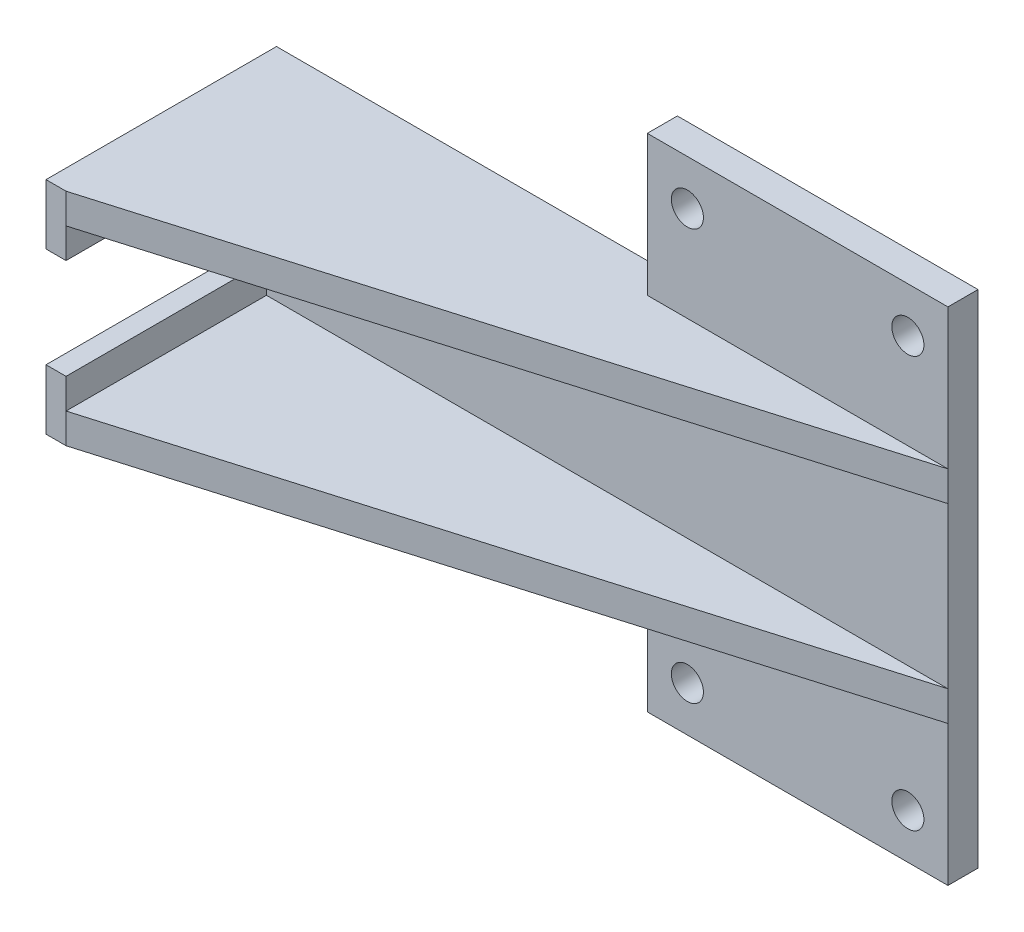
SolidWorks part; units mm, degrees
ref_plane "前视基准面" through (0, 0, 0) normal (0, 0, 1) x (1, 0, 0)
ref_plane "上视基准面" through (0, 0, 0) normal (0, 1, 0) x (1, 0, 0)
ref_plane "右视基准面" through (0, 0, 0) normal (1, 0, 0) x (0, 0, -1)
other "Configuration Table"
sketch "草图1" plane through (0, 0, 0) normal (0, 0, 1) x (1, 0, 0)
  line L0 (-40, -15) -> (-110.8867, -15) construction
  line L1 (-10, 10) -> (-40, 10)
  line L2 (-10, 10) -> (-10, -40)
  line L3 (-10, -40) -> (-40, -40)
  line L4 (-40, 10) -> (-40, -7)
  line L5 (-40, -23) -> (-40, -40)
  line L6 (-80, -23) -> (-40, -23)
  line L7 (-80, -23) -> (-80, -7)
  line L8 (-80, -7) -> (-40, -7)
  line L10 (-80, -23) -> (-40, -7) construction
  line L11 (-80, -7) -> (-40, -23) construction
  circle A0 centre (-14, -35.5) radius 1.6
  circle A1 centre (-36, 5.5) radius 1.6
  circle A2 centre (-36, -35.5) radius 1.6
  circle A3 centre (-14, 5.5) radius 1.6
  point P20 (-60, -15)
  dimension "D1" = 40
  dimension "D2" = 16
extrude "凸台-拉伸1" add sketch "草图1" along normal blind 3
sketch "草图5" plane through (0, 0, 3) normal (0, 0, 1) x (1, 0, 0)
  line L1 (-80, -23) -> (-78, -23)
  line L2 (-80, -23) -> (-80, -20)
  line L3 (-80, -20) -> (-78, -20)
  line L4 (-78, -23) -> (-78, -20)
  line L5 (-80, -7) -> (-78, -7)
  line L6 (-80, -7) -> (-80, -10)
  line L7 (-80, -10) -> (-78, -10)
  line L8 (-78, -7) -> (-78, -10)
  dimension "D1" = 2
  dimension "D2" = 3
  dimension "D3" = 2
  dimension "D4" = 3
extrude "凸台-拉伸3" add sketch "草图5" along normal blind 20
sketch "草图7" plane through (0, -7, 0) normal (0, 1, 0) x (1, 0, 0)
  line L0 (-78, -23) -> (-10, -3)
  line L1 (-10, -3) -> (-40, -3) construction
  line L4 (-78, -23) -> (-80, -23)
  line L5 (-80, -23) -> (-80, 0)
  line L6 (-80, 0) -> (-40, 0)
  line L7 (-40, 0) -> (-40, -3)
  line L8 (-40, -3) -> (-10, -3)
  line L9 (-10, -3) -> (-10, 0) construction
  point P5 (-31.2572, -3)
  point P15 (-10, -3)
extrude "凸台-拉伸4" add sketch "草图7" along normal blind 3
ref_plane "基准面1" through (0, -15, 0) normal (0, -1, 0) x (-1, 0, 0)
mirror "镜向1" about plane through (0, -15, 0) normal (0, -1, 0) of "凸台-拉伸4"
